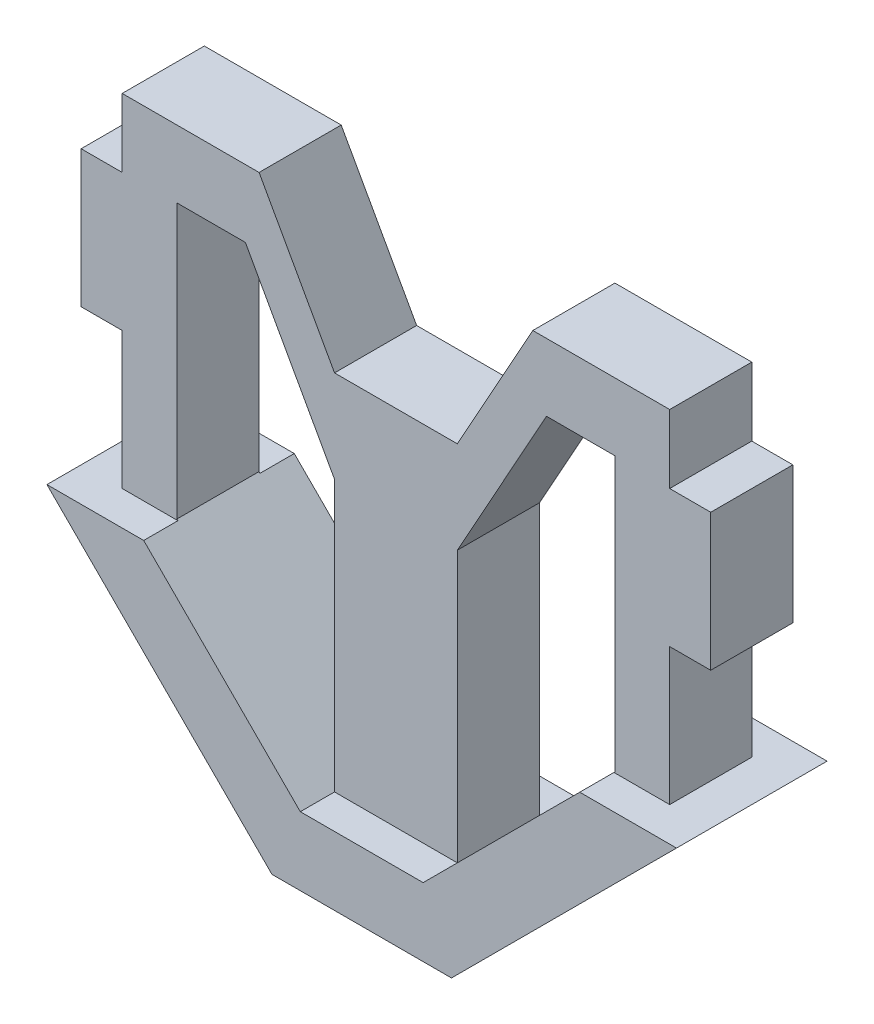
SolidWorks part; units mm, degrees
material "PE High Density"
ref_plane "Front Plane" through (0, 0, 0) normal (0, 0, 1) x (1, 0, 0)
ref_plane "Top Plane" through (0, 0, 0) normal (0, 1, 0) x (1, 0, 0)
ref_plane "Right Plane" through (0, 0, 0) normal (1, 0, 0) x (0, 0, -1)
sketch "Sketch1" plane through (0, 0, 0) normal (0, 0, 1) x (1, 0, 0)
  line L0 (-20, -12.5) -> (-23, -12.5)
  line L1 (-20, 12.5) -> (-10, 12.5)
  line L2 (-20, 12.5) -> (-20, 7.5)
  line L3 (-16.0006, -12.4283) -> (-4.4871, -23.9419)
  line L4 (20, 12.5) -> (20, 7.5)
  line L5 (16.0006, -12.4283) -> (4.4871, -23.9419)
  line L6 (-16.0006, -12.4283) -> (-16.0006, 7.5717)
  line L7 (-20, 7.5) -> (-23, 7.5)
  line L9 (-20, -2.5) -> (-23, -2.5)
  line L10 (-23, 7.5) -> (-23, -2.5)
  line L11 (20, 7.5) -> (23, 7.5)
  line L12 (-20, -2.5) -> (-20, -12.5)
  line L13 (20, -2.5) -> (23, -2.5)
  line L14 (23, 7.5) -> (23, -2.5)
  line L15 (20, -12.5) -> (23, -12.5)
  line L16 (-23, -12.5) -> (-6.5581, -28.9419)
  line L17 (6.5581, -28.9419) -> (23, -12.5)
  line L18 (-6.5581, -28.9419) -> (6.5581, -28.9419)
  line L19 (-4.4871, -23.9419) -> (-4.4871, -4.1586)
  line L20 (4.4871, -23.9419) -> (4.4871, -4.1586)
  line L21 (10, 12.5) -> (4.4871, 2.5717)
  line L22 (-10, 12.5) -> (-4.4871, 2.5717)
  line L23 (10, 12.5) -> (20, 12.5)
  line L24 (-4.4871, 2.5717) -> (4.4871, 2.5717)
  line L25 (16.0006, -12.4283) -> (16.0006, 7.5717)
  line L26 (16.0006, 7.5717) -> (11.0006, 7.5717)
  line L27 (-16.0006, 7.5717) -> (-11.0006, 7.5717)
  line L28 (-11.0006, 7.5717) -> (-4.4871, -4.1586)
  line L29 (11.0006, 7.5717) -> (4.4871, -4.1586)
  line L30 (20, -2.5) -> (20, -12.5)
  point P0 (0, 0)
  dimension "D1" = 40
  dimension "D2" = 25
  dimension "D3" = 5
  dimension "D5" = 10
  dimension "D8" = 3
  dimension "D11" = 5
  dimension "D12" = 5
  dimension "D14" = 5
  dimension "D15" = 5
  dimension "D17" = 10
  dimension "D18" = 4
  dimension "D20" = 20
  dimension "D22" = 5
extrude "Boss-Extrude1" add sketch "Sketch1" along normal blind 6
sketch "Sketch2" plane through (0, 0, 6) normal (0, 0, 1) x (1, 0, 0)
  line L0 (-23, -12.5) -> (-6.5581, -28.9419)
  line L1 (-6.5581, -28.9419) -> (6.5581, -28.9419)
  line L2 (6.5581, -28.9419) -> (23, -12.5)
  line L3 (23, -12.5) -> (15.9289, -12.5)
  line L5 (-16.0006, -12.4283) -> (-4.4871, -23.9419) construction
  line L6 (4.4871, -23.9419) -> (16.0006, -12.4283) construction
  line L7 (10.2439, -18.1851) -> (4.4871, -23.9419)
  line L8 (4.4871, -23.9419) -> (-4.4871, -23.9419)
  line L9 (-4.4871, -23.9419) -> (-10.2439, -18.1851)
  line L10 (-10.2439, -18.1851) -> (-15.9289, -12.5)
  line L11 (10.2439, -18.1851) -> (15.9289, -12.5)
  line L12 (-15.9289, -12.5) -> (-23, -12.5)
extrude "Boss-Extrude2" add sketch "Sketch2" along normal blind 2.5 and the other way blind 8.5
